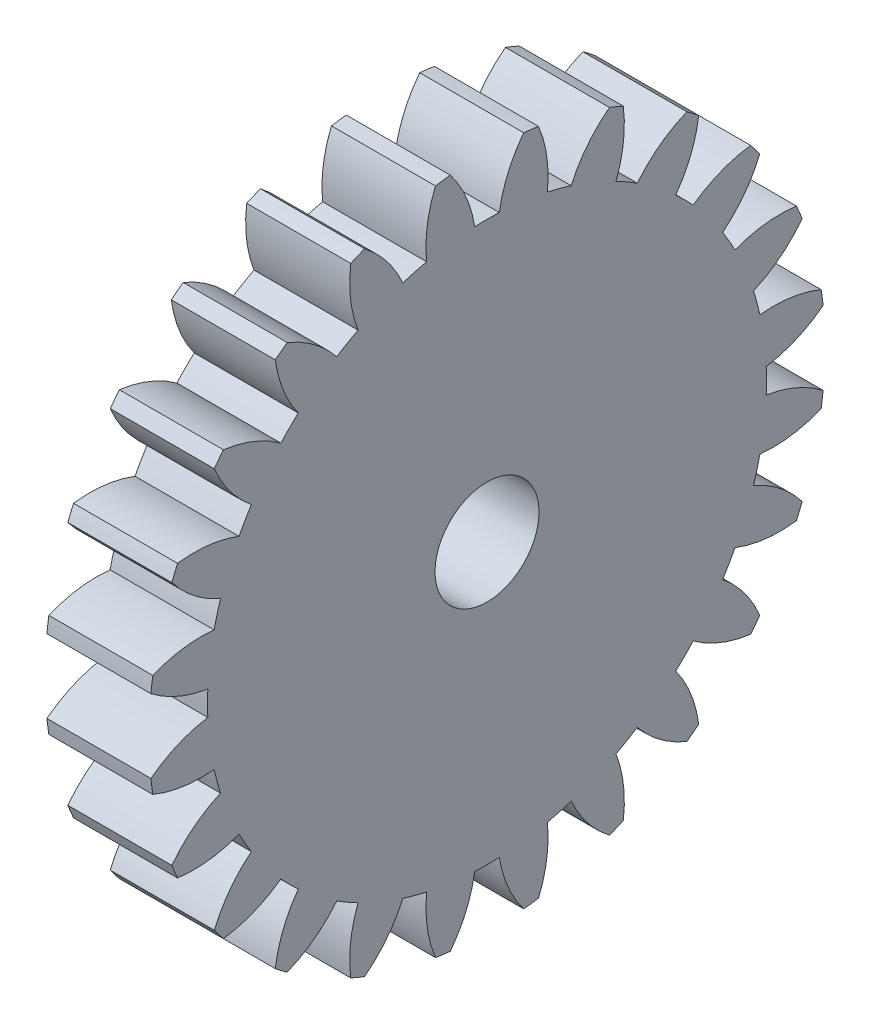
SolidWorks part; units mm, degrees
ref_plane "Plane1" through (0, 0, 0) normal (0, 0, 1) x (1, 0, 0)
ref_plane "Plane2" through (0, 0, 0) normal (0, 1, 0) x (1, 0, 0)
ref_plane "Plane3" through (0, 0, 0) normal (1, 0, 0) x (0, 0, -1)
sketch "HoldingSke" plane through (0, 0, 0) normal (0, 1, 0) x (1, 0, 0)
  line L0 (0, 0) -> (3.6542, -1.6269)
  line L1 (-15, 0) -> (100, 0) construction
  line L2 (0, 0) -> (-2.1039, 2.3779)
  line L3 (0, 0) -> (-11.863, 4.5341)
  line L4 (0, 0) -> (7.8894, 3.5126)
  line L5 (0, 0) -> (-46.8476, -17.4728)
  line L6 (0, 0) -> (-0.829, -0.5593)
  line L7 (-2.1039, 2.3779) -> (8.6586, 51.2059)
  line L8 (-76.2, 54.61) -> (-76.1, 54.61)
  line L9 (-71.009, 38.7566) -> (-53.1078, 45.2721)
  line L10 (-76.2, 71.12) -> (104.1128, 71.12)
  line L11 (0, 0) -> (-1, 0)
  line L12 (-76.2, 101.6) -> (-76.192, 101.6)
  line L13 (24.9733, 27.94) -> (52.9518, 28.4284)
  line L14 (24.9733, 27.94) -> (24.9743, 27.94)
  line L15 (24.9733, 27.94) -> (100.4006, 29.5858)
  line L16 (-63.627, -0.25) -> (-12.827, -0.25)
  circle A0 centre (0, 0) radius 0.625
  circle A1 centre (0, 0) radius 2.6865
  circle A2 centre (0, 0) radius 37.5
  circle A3 centre (0, 0) radius 0.625
  dimension "MHD" = 5.373
  dimension "Hub_dia" = 75
  dimension "Bore" = 1.25
  dimension "MBD" = 1.25
  dimension "Num_teeth" = 24
  dimension "Pitch" = 4
  dimension "Overall_len" = 50
  dimension "Show_teeth" = 24
  dimension "Thickness" = 1
  dimension "OAL" = 50.0001
  dimension "T_dim" = 0.1
  dimension "Ap" = 20
  dimension "H" = 19.05
  dimension "Pitch_radius" = 180.3128
  dimension "Width" = 1
  dimension "Backlash" = 0.008
  dimension "Addendum_fac" = 1
  dimension "Dedendum_fac" = 1.25
  dimension "Clearance_fac" = 0.25
  dimension "Dedendum_add" = 0.001
  dimension "Module" = 0.25
sketch "BasProSke" plane through (0, 0, 0) normal (0, 1, 0) x (1, 0, 0)
  line L0 (-10, 0) -> (60, 0) construction
  line L1 (0, 0) -> (0, 3.25)
  line L2 (0, 0) -> (1, 0)
  line L3 (1, 0) -> (1, 3.25)
  line L4 (1, 3.25) -> (0, 3.25)
  dimension "Thickness" = 1
  dimension "Diameter" = 6.5
revolve "Base-Revolve" add sketch "BasProSke" angle 360 about L0
sketch "TooCutSke" plane through (0, 0, 0) normal (1, 0, 0) x (0, 0, -1)
  line L1 (0, 0) -> (0, 107) construction
  line L2 (0, 0) -> (-0.2102, 2.9926) construction
  line L3 (0, 0) -> (-0.7817, 5.9377) construction
  line L4 (-0.2102, 2.9926) -> (-0.3909, 2.9688) construction
  arc A0 (0.1184, 2.6839) -> (-0.1184, 2.6839) centre (0, 0) ccw
  arc A1 (0.3714, 3.2543) -> (-0.3714, 3.2543) centre (0, 0) ccw
  circle A2 centre (0, 0) radius 3 construction
  circle A3 centre (0, 0) radius 2.8191 construction
  arc A4 (-0.1184, 2.6839) -> (-0.3714, 3.2543) centre (-1.3041, 2.4993) ccw
  arc A5 (0.3714, 3.2543) -> (0.1184, 2.6839) centre (1.3041, 2.4993) ccw
  dimension "Root_dia" = 5.373
  dimension "Overcut_dia" = 6.5508
  dimension "Pitch_dia" = 6
  dimension "Base_dia" = 5.6382
  dimension "Flank_rad" = 1.2
  dimension "Half_ang" = 7.5
  dimension "Half_CT" = 0.1822
extrude "ToothCut" cut sketch "TooCutSke" along normal through all
fillet "Breaks" [suppressed] radius 0.005
fillet "RootFillets" [suppressed] radius 0.0635
pattern_circular "TeethCuts" count 24 every 15 about axis through (-10, 0, 0) along (1, 0, 0) of "ToothCut", "RootFillets", "Breaks"
sketch "HubNeaOneSke" plane through (0, 0, 0) normal (-1, 0, 0) x (0, 0, 1)
  circle A0 centre (0, 0) radius 2.6865
  dimension "Diameter" = 5.373
extrude "HubNearOne" [suppressed] add sketch "HubNeaOneSke" along normal blind 49.0001
sketch "HubNeaBotSke" plane through (0, 0, 0) normal (-1, 0, 0) x (0, 0, 1)
  circle A0 centre (0, 0) radius 2.6865
  dimension "Diameter" = 5.373
extrude "HubNearBoth" [suppressed] add sketch "HubNeaBotSke" along normal blind 24.5
ref_plane "FarPln" through (1, 0, 0) normal (1, 0, 0) x (0, 0, -1)
sketch "HubFarSke" plane through (1, 0, 0) normal (1, 0, 0) x (0, 0, -1)
  circle A0 centre (0, 0) radius 2.6865
  dimension "Diameter" = 5.373
extrude "HubFar" [suppressed] add sketch "HubFarSke" along normal blind 24.5
sketch "BorSke" plane through (0, 0, 0) normal (1, 0, 0) x (0, 0, -1)
  circle A0 centre (0, 0) radius 0.5
  dimension "Diameter" = 1
extrude "Bore" cut sketch "BorSke" along normal mid plane 100.0001
sketch "KeySke" plane through (0, 0, 0) normal (1, 0, 0) x (0, 0, -1)
  line L0 (-0.05, 0) -> (-0.05, 0.725)
  line L1 (-0.05, 0.725) -> (0.05, 0.725)
  line L2 (0.05, 0.725) -> (0.05, 0)
  line L3 (0, 0) -> (0, 34) construction
  line L4 (-0.05, 0) -> (0.05, 0)
  dimension "Offset" = 0.725
extrude "Keyway" [suppressed] cut sketch "KeySke" along normal mid plane 100.0001
pattern_circular "Keyway2" [suppressed] count 2 every 90 about axis through (-10, 0, 0) along (1, 0, 0)
equation "' \"Module@HoldingSke\" = 6.35"
equation "' \"Num_teeth@HoldingSke\" = 12"
equation "' \"Ap@HoldingSke\" =  20"
equation "' \"Ap@HoldingSke\" = 20"
equation "' \"Width@HoldingSke\" = 0.5 * 25.4"
equation "' \"Hub_dia@HoldingSke\"= 1 * 25.4"
equation "' \"Hub_dia@HoldingSke\" = 1 * 25.4"
equation "' \"Overall_len@HoldingSke\" = 1.0 * 25.4"
equation "' \"Bore@HoldingSke\" = 0.75 * 25.4"
equation "' \"T_dim@HoldingSke\" = 0.1 * 25.4"
equation "' \"Width@KeySke\" = 0.25 * 25.4"
equation "' \"Show_teeth@HoldingSke\" = 13"
equation "' \"Backlash@HoldingSke\" = 0.009 * 25.4"
equation "' \"Addendum_fac@HoldingSke\" = 1.0"
equation "' \"Dedendum_fac@HoldingSke\" = 1.25"
equation "' \"Dedendum_add@HoldingSke\" = 0.00005 * 25.4"
equation "' \"Clearance_fac@HoldingSke\" = 0.25"
equation "\"Pitch@HoldingSke\" = 1 / \"Module@HoldingSke\""
equation "\"Overcut_dia@TooCutSke\" = (\"Num_teeth@HoldingSke\" + 2 * \"Addendum_fac@HoldingSke\") / \"Pitch@HoldingSke\" + 0.002 * 25.4"
equation "\"Pitch_dia@TooCutSke\" = \"Num_teeth@HoldingSke\" / \"Pitch@HoldingSke\""
equation "\"Base_dia@TooCutSke\" = \"Num_teeth@HoldingSke\" / \"Pitch@HoldingSke\" * cos((\"Ap@HoldingSke\"  * 3.14159265 / 180))"
equation "\"Root_dia@TooCutSke\" = (\"Num_teeth@HoldingSke\" + 2) / \"Pitch@HoldingSke\" - 2 * (\"Addendum_fac@HoldingSke\" + \"Dedendum_fac@HoldingSke\") / \"Pitch@HoldingSke\" - \"Dedendum_add@HoldingSke\" * 2"
equation "\"Half_ang@TooCutSke\" = 180 / \"Num_teeth@HoldingSke\""
equation "\"Half_CT@TooCutSke\" = \"Num_teeth@HoldingSke\" / \"Pitch@HoldingSke\" * sin((3.14159265 / 2 / \"Num_teeth@HoldingSke\")) / 2 - 7 * \"Backlash@HoldingSke\" / 4"
equation "\"Flank_rad@TooCutSke\" = \"Num_teeth@HoldingSke\" / \"Pitch@HoldingSke\" / 5"
equation "\"Radius@RootFillets\" = \"Clearance_fac@HoldingSke\" / \"Pitch@HoldingSke\" + \"Dedendum_add@HoldingSke\""
equation "\"Break_rad@Breaks\" = 0.02 / \"Pitch@HoldingSke\""
equation "\"Thickness@HoldingSke\" = \"Width@HoldingSke\""
equation "\"OAL@HoldingSke\" = \"Thickness@HoldingSke\""
equation "\"MHD@HoldingSke\" = (\"Num_teeth@HoldingSke\" + 2) / \"Pitch@HoldingSke\" - 2 * (\"Addendum_fac@HoldingSke\" + \"Dedendum_fac@HoldingSke\")  / \"Pitch@HoldingSke\" - \"Dedendum_add@HoldingSke\" * 2"
equation "\"MBD@HoldingSke\" = (\"Num_teeth@HoldingSke\" + 2) / \"Pitch@HoldingSke\" - 2 * (\"Addendum_fac@HoldingSke\" + \"Dedendum_fac@HoldingSke\")  / \"Pitch@HoldingSke\" - \"Dedendum_add@HoldingSke\" * 2 - 0.002 * 25.4"
equation "\"MHD@HoldingSke\" = ((sgn( \"MHD@HoldingSke\" - \"Hub_dia@HoldingSke\" )-1)*( \"MHD@HoldingSke\" - \"Hub_dia@HoldingSke\" ))/-2+ \"Hub_dia@HoldingSke\""
equation "\"MBD@HoldingSke\" = ((sgn( \"MBD@HoldingSke\" - \"Bore@HoldingSke\" )-1)*( \"MBD@HoldingSke\" - \"Bore@HoldingSke\" ))/-2+ \"Bore@HoldingSke\""
equation "\"OAL@HoldingSke\" = ((sgn( \"OAL@HoldingSke\" - \"Overall_len@HoldingSke\" )+1)*( \"OAL@HoldingSke\" - \"Overall_len@HoldingSke\" ))/2 + \"Overall_len@HoldingSke\" + 0.000002 * 25.4"
equation "\"Num_teeth@TeethCuts\" = int( \"Show_teeth@HoldingSke\" ) + 1"
equation "\"Num_teeth@TeethCuts\" = ((sgn( \"Num_teeth@TeethCuts\" - \"Num_teeth@HoldingSke\" )-1)*( \"Num_teeth@TeethCuts\" - \"Num_teeth@HoldingSke\" ))/-2+ \"Num_teeth@HoldingSke\""
equation "\"Num_teeth@TeethCuts\" = ((sgn( \"Num_teeth@TeethCuts\" - 2.0)+1)*( \"Num_teeth@TeethCuts\" - 2.0))/2 +2.0"
equation "\"Angle@TeethCuts\" = 360.0 / \"Num_teeth@HoldingSke\""
equation "\"Diameter@BasProSke\" = (\"Num_teeth@HoldingSke\" + 2 * \"Addendum_fac@HoldingSke\") / \"Pitch@HoldingSke\""
equation "\"Thickness@BasProSke\"  = \"Thickness@HoldingSke\""
equation "' \"Fillet_rad@BasProSke\" =  \"Thickness@HoldingSke\" * 0.05"
equation "' \"Fillet_rad@BasProSke\" = \"Thickness@HoldingSke\" * 0.05"
equation "\"MHD@HoldingSke\" = ((sgn( \"MHD@HoldingSke\" - \"Root_dia@TooCutSke\" )-1)*( \"MHD@HoldingSke\" - \"Root_dia@TooCutSke\" ))/-2+ \"Root_dia@TooCutSke\""
equation "\"Diameter@HubNeaOneSke\" = \"MHD@HoldingSke\""
equation "\"Length@HubNearOne\" = \"OAL@HoldingSke\" - \"Thickness@BasProSke\""
equation "\"Diameter@HubNeaBotSke\" = \"MHD@HoldingSke\""
equation "\"Length@HubNearBoth\" = ( \"OAL@HoldingSke\" - \"Thickness@BasProSke\" ) / 2.0"
equation "\"Thickness@FarPln\" = \"Thickness@BasProSke\""
equation "\"Diameter@HubFarSke\" = \"MHD@HoldingSke\""
equation "\"Length@HubFar\" = ( \"OAL@HoldingSke\" - \"Thickness@BasProSke\" ) / 2.0"
equation "\"D1@Bore\" = \"OAL@HoldingSke\" * 2.0"
equation "\"D1@Keyway\" = \"OAL@HoldingSke\" * 2.0"
equation "\"Offset@KeySke\" = \"T_dim@HoldingSke\" + \"MBD@HoldingSke\" / 2.0"
